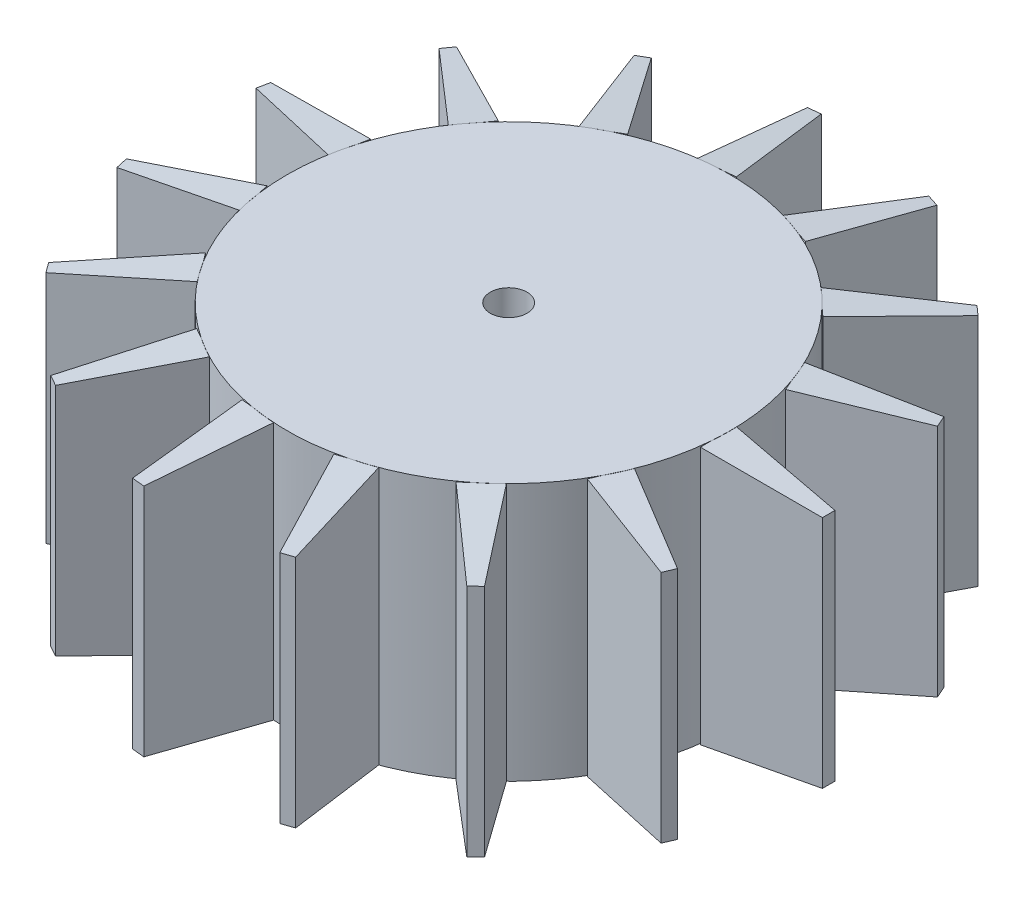
SolidWorks part; units mm, degrees
ref_plane "Front Plane" through (0, 0, 0) normal (0, 0, 1) x (1, 0, 0)
ref_plane "Top Plane" through (0, 0, 0) normal (0, 1, 0) x (1, 0, 0)
ref_plane "Right Plane" through (0, 0, 0) normal (1, 0, 0) x (0, 0, -1)
sketch "Sketch1" plane through (0, 0, 0) normal (0, 1, 0) x (1, 0, 0)
  circle A0 centre (0, 0) radius 40.4653
  circle A1 centre (0, 0) radius 60.1972
extrude "Boss-Extrude1" add sketch "Sketch1" along normal blind 70
ref_plane "Plane2" through (60, 0, 0) normal (1, 0, 0) x (0, 0, -1)
sketch "Sketch3" plane through (60, 0, 0) normal (1, 0, 0) x (0, 0, -1)
  line L0 (60.1972, 70) -> (-60.1972, 70) construction
  line L1 (-7.9444, 70) -> (1.7654, 70)
  line L2 (-7.9444, 70) -> (-7.9444, 0)
  line L3 (-7.9444, 0) -> (1.7654, 0)
  line L4 (1.7654, 70) -> (1.7654, 0)
extrude "Boss-Extrude2" add sketch "Sketch3" along normal blind 30 draft 6
sketch "Sketch4" plane through (90, 0, 0) normal (1, 0, 0) x (0, 0, -1)
  line L0 (-1.3877, 3.1531) -> (-1.3877, 66.8469) construction
  line L1 (-4.7913, 66.8469) -> (-1.3877, 66.8469)
  line L2 (-4.7913, 66.8469) -> (-4.7913, 3.3992)
  line L3 (-4.7913, 3.3992) -> (-1.3877, 3.3992)
  line L4 (-1.3877, 66.8469) -> (-1.3877, 3.3992)
pattern_circular "CirPattern2" count 15 over 337 about axis through (0, 0, 0) along (0, 1, 0) of "Boss-Extrude2"
sketch "Sketch5" plane through (0, 70, 0) normal (0, 1, 0) x (1, 0, 0)
  circle A0 centre (0, 0) radius 40.4653
  circle A1 centre (0, 0) radius 4.9853
extrude "Boss-Extrude3" add sketch "Sketch5" against normal blind 70
